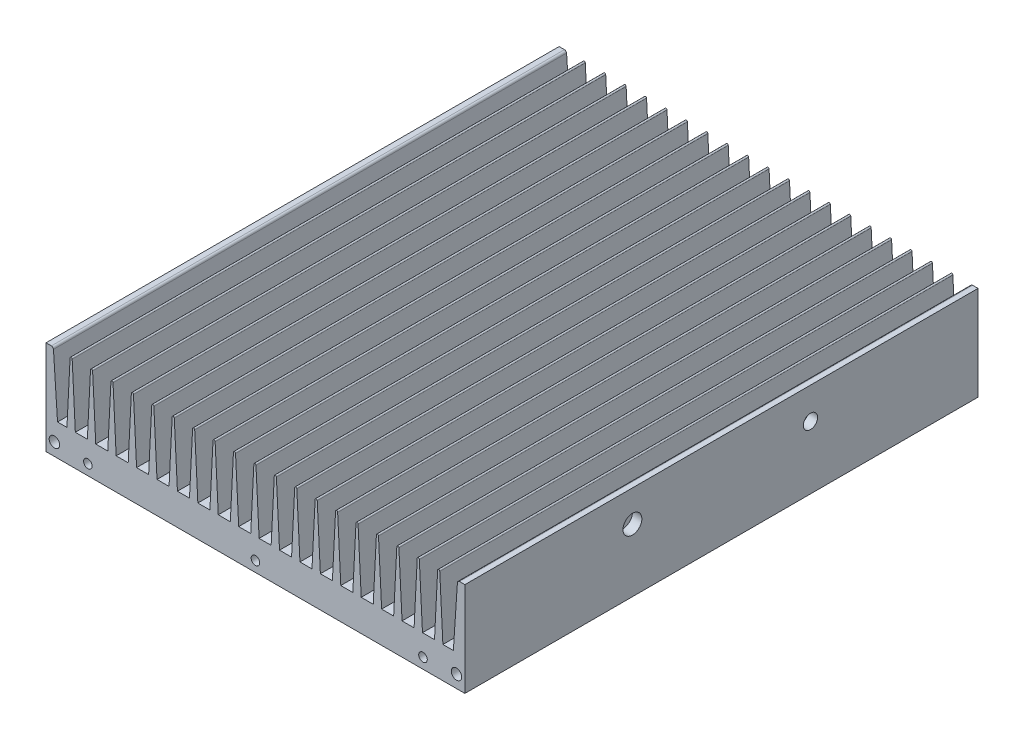
SolidWorks part; units mm, degrees
ref_plane "Спереди" through (0, 0, 0) normal (0, 0, 1) x (1, 0, 0)
ref_plane "Сверху" through (0, 0, 0) normal (0, 1, 0) x (1, 0, 0)
ref_plane "Справа" through (0, 0, 0) normal (1, 0, 0) x (0, 0, -1)
sketch "Эскиз1" plane through (0, 0, 0) normal (0, 0, 1) x (1, 0, 0)
  line L0 (0, 45) -> (2.5644, 45)
  line L1 (0, 0) -> (200, 0)
  line L2 (3.5622, 44.0665) -> (5.5, 15)
  line L3 (0, 45) -> (0, 0)
  line L4 (200, 45) -> (200, 0)
  line L5 (100, 63.7127) -> (100, -22.2582) construction
  line L8 (200, 45) -> (197.4356, 45)
  line L9 (196.4378, 44.0665) -> (194.5, 15)
  line L10 (5.5, 15) -> (194.5, 15)
  arc A0 (2.5644, 45) -> (3.5622, 44.0665) centre (2.5644, 44) cw
  arc A2 (197.4356, 45) -> (196.4378, 44.0665) centre (197.4356, 44) ccw
  point P18 (196.5, 45)
  dimension "D9" = 1
  dimension "D1" = 200
  dimension "D2" = 15
  dimension "D3" = 45
  dimension "D4" = 5.5
  dimension "D7" = 3.5
extrude "Вытянуть1" add sketch "Эскиз1" along normal blind 245
sketch "Эскиз2" plane through (0, 0, 245) normal (0, 0, 1) x (1, 0, 0)
  line L0 (194.5, 15) -> (5.5, 15) construction
  line L1 (11.5, 44.5) -> (10, 15)
  line L2 (12, 44.5) -> (12, 22.5548) construction
  line L3 (12.5, 44.5) -> (14, 15)
  line L4 (10, 15) -> (14, 15)
  line L6 (0, 45) -> (0, 0) construction
  arc A0 (11.5, 44.5) -> (12.5, 44.5) centre (12, 44.5) cw
  dimension "D1" = 30
  dimension "D3" = 0.5
  dimension "D2" = 4
  dimension "D4" = 12
  dimension "D5" = 1
extrude "Вытянуть3" add sketch "Эскиз2" against normal blind 245
pattern_curve "Кривая1" of "Вытянуть3" along edge at (100, 0, 0) parameters "D1"=19, "D3"=9.75, "D2"=1, "D4"=50
sketch "Эскиз3" plane through (0, 0, 245) normal (0, 0, 1) x (1, 0, 0)
  line L0 (-5.713, 5) -> (205.713, 5) construction
  line L1 (100, 80.0798) -> (100, -21.2847) construction
  line L2 (0, 45) -> (0, 0) construction
  line L3 (200, 0) -> (200, 45) construction
  line L4 (0, 0) -> (200, 0) construction
  circle A0 centre (20, 5) radius 2.05
  circle A1 centre (100, 5) radius 2.05
  circle A2 centre (180, 5) radius 2.05
  dimension "D2" = 4.1
  dimension "D1" = 5
  dimension "D3" = 20
extrude "Вырез-Вытянуть1" cut sketch "Эскиз3" against normal blind 10
cosmetic thread "Условное изображение резьбы14" parameters "D1"=10, "D2"=5
cosmetic thread "Условное изображение резьбы15" parameters "D1"=10, "D2"=5
cosmetic thread "Условное изображение резьбы16" parameters "D1"=10, "D2"=5
sketch "Эскиз5" plane through (0, 0, 0) normal (0, 0, -1) x (-1, 0, 0)
  circle A0 centre (-180, 5) radius 2.05 construction
  circle A1 centre (-180, 5) radius 2.05
  circle A2 centre (-100, 5) radius 2.05 construction
  circle A3 centre (-100, 5) radius 2.05
  circle A4 centre (-20, 5) radius 2.05 construction
  circle A5 centre (-20, 5) radius 2.05
extrude "Вырез-Вытянуть2" cut sketch "Эскиз5" against normal blind 10
cosmetic thread "Условное изображение резьбы20" parameters "D1"=10, "D2"=5
cosmetic thread "Условное изображение резьбы21" parameters "D1"=10, "D2"=5
cosmetic thread "Условное изображение резьбы22" parameters "D1"=10, "D2"=5
sketch "Эскиз6" plane through (0, 0, 0) normal (0, 0, -1) x (-1, 0, 0)
  line L0 (0, 0) -> (-200, 0) construction
  line L1 (0, 45) -> (0, 0) construction
  line L2 (-200, 0) -> (-200, 45) construction
  circle A0 centre (-4, 6) radius 2.5
  circle A1 centre (-196, 6) radius 2.5
  dimension "D1" = 5
  dimension "D2" = 6
  dimension "D3" = 4
  dimension "D6" = 5
  dimension "D4" = 4
  dimension "D5" = 6
extrude "Вырез-Вытянуть3" cut sketch "Эскиз6" against normal blind 8
sketch "Эскиз7" plane through (0, 0, 0) normal (-1, 0, 0) x (0, 0, 1)
  line L0 (-24.1676, 20) -> (275.3481, 20) construction
  line L1 (122.5, 109.9776) -> (122.5, -31.6981) construction
  line L2 (245, 45) -> (245, 0) construction
  line L3 (0, 45) -> (0, 0) construction
  line L4 (245, 0) -> (0, 0) construction
  circle A0 centre (22.5, 20) radius 2.6
  circle A1 centre (222.5, 20) radius 2.6
  circle A2 centre (122.5, 20) radius 2.6
  dimension "D2" = 5.2
  dimension "D3" = 200
  dimension "D1" = 20
extrude "Вырез-Вытянуть4" cut sketch "Эскиз7" against normal blind 6
cosmetic thread "Условное изображение резьбы17" parameters "D1"=5.26, "D2"=6
cosmetic thread "Условное изображение резьбы18" parameters "D1"=5.26, "D2"=6
cosmetic thread "Условное изображение резьбы19" parameters "D1"=5.26, "D2"=6
sketch "Эскиз8" plane through (200, 0, 0) normal (1, 0, 0) x (0, 0, -1)
  line L0 (9.57, 30) -> (-255.3048, 30) construction
  line L1 (-245, 45) -> (0, 45) construction
  line L2 (-122.5, 20) -> (-122.5, -38.851) construction
  line L3 (0, 0) -> (0, 45) construction
  line L4 (-245, 0) -> (-245, 45) construction
  circle A0 centre (-80, 30) radius 3.4
  circle A1 centre (-165, 30) radius 4.5
  dimension "D2" = 6.8
  dimension "D3" = 9
  dimension "D5" = 80
  dimension "D1" = 15
  dimension "D4" = 80
extrude "Вырез-Вытянуть5" cut sketch "Эскиз8" against normal blind 6
cosmetic thread "Условное изображение резьбы13" parameters "D1"=3, "D2"=8
sketch "Эскиз10" plane through (0, 0, 245) normal (0, 0, 1) x (1, 0, 0)
  circle A0 centre (196, 6) radius 2.5 construction
  circle A1 centre (196, 6) radius 2.5
  circle A2 centre (4, 6) radius 2.5 construction
  circle A3 centre (4, 6) radius 2.5
extrude "Вырез-Вытянуть7" cut sketch "Эскиз10" against normal blind 8
sketch "Эскиз12" plane through (0, 0, 0) normal (0, -1, 0) x (1, 0, 0)
  line L1 (0, 245) -> (200, 245) construction
  line L11 (0, 245) -> (0, 0) construction
  line L12 (10, 235) -> (10, 99.1924) construction
  line L14 (10, 235) -> (42.5, 235) construction
  line L15 (10, 125) -> (173.6844, 125) construction
  line L16 (160, 235) -> (160, 71.315) construction
  line L17 (100.5, 203) -> (143.5169, 203) construction
  line L18 (100.5, 203) -> (100.5, 168.1355) construction
  line L19 (100.5, 158) -> (127.493, 158) construction
  line L20 (130, 203) -> (130, 150.4747) construction
  circle A0 centre (45.75, 202.5) radius 1.3
  circle A10 centre (10, 235) radius 1.6
  circle A12 centre (10, 125) radius 1.6
  circle A13 centre (160, 235) radius 1.6
  circle A14 centre (160, 125) radius 1.6
  circle A15 centre (75, 225) radius 2.1
  circle A17 centre (100.5, 203) radius 1.3
  circle A18 centre (100.5, 158) radius 1.3
  circle A19 centre (130, 203) radius 1.3
  circle A20 centre (130, 158) radius 1.3
  dimension "D23" = 110
  dimension "D24" = 4.2
  dimension "D25" = 85
  dimension "D26" = 10
  dimension "D20" = 10
  dimension "D19" = 3.2
  dimension "D21" = 10
  dimension "D22" = 150
  dimension "D32" = 29.5
  dimension "D33" = 45
  dimension "D34" = 2.6
  dimension "D4" = 32.5
  dimension "D5" = 35.75
  dimension "D35" = 33
  dimension "D36" = 30
extrude "Вырез-Вытянуть8" cut sketch "Эскиз12" against normal blind 8
cosmetic thread "Условное изображение резьбы23" parameters "D1"=8, "D2"=4
cosmetic thread "Условное изображение резьбы24" parameters "D1"=8, "D2"=4
cosmetic thread "Условное изображение резьбы25" parameters "D1"=8, "D2"=4
cosmetic thread "Условное изображение резьбы26" parameters "D1"=8, "D2"=4
cosmetic thread "Условное изображение резьбы27" parameters "D1"=8, "D2"=3
cosmetic thread "Условное изображение резьбы28" parameters "D1"=8, "D2"=3
cosmetic thread "Условное изображение резьбы29" parameters "D1"=8, "D2"=3
cosmetic thread "Условное изображение резьбы30" parameters "D1"=8, "D2"=3
cosmetic thread "Условное изображение резьбы31" parameters "D1"=8, "D2"=5
cosmetic thread "Условное изображение резьбы33" parameters "D1"=8, "D2"=3
